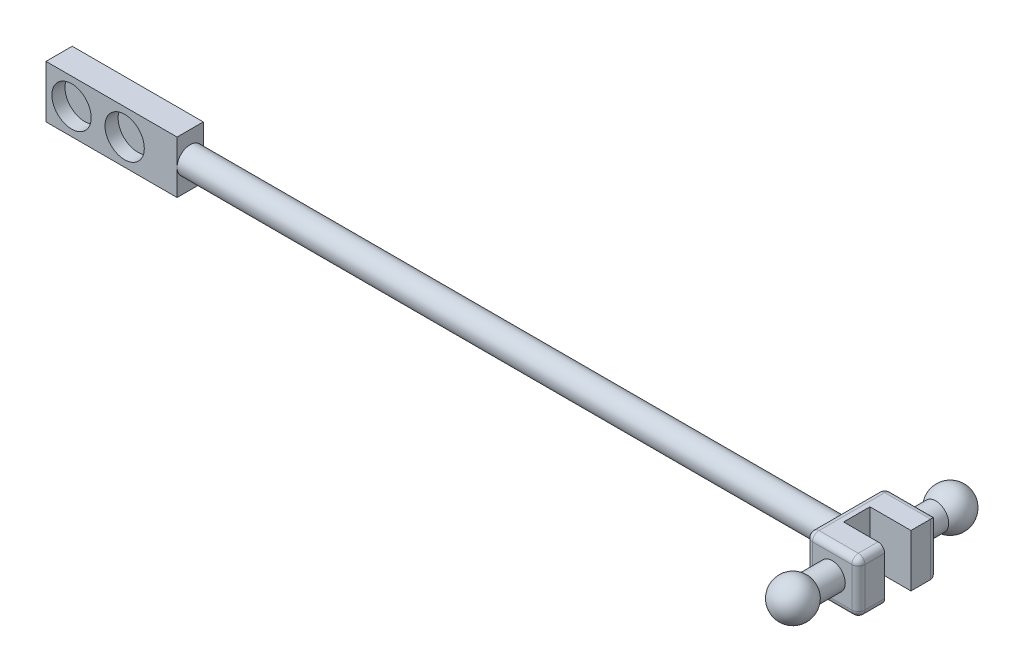
SolidWorks part; units mm, degrees
ref_plane "Front Plane" through (0, 0, 0) normal (0, 0, 1) x (1, 0, 0)
ref_plane "Top Plane" through (0, 0, 0) normal (0, 1, 0) x (1, 0, 0)
ref_plane "Right Plane" through (0, 0, 0) normal (1, 0, 0) x (0, 0, -1)
sketch "Sketch1" plane through (0, 0, 0) normal (0, 0, 1) x (1, 0, 0)
  line L0 (-95.2278, -7.0496) -> (-85.2278, -7.0496)
  line L1 (-85.2278, -7.0496) -> (-85.2278, -11.0496)
  line L2 (-95.2278, -7.0496) -> (-95.2278, -11.0496)
  line L3 (-1049.8238, -9.0496) -> (48950.1762, -9.0496) construction
  line L4 (-95.2278, -11.0496) -> (-85.2278, -11.0496)
  point P7 (-85.2278, -9.0496)
  point P8 (-95.2278, -9.0496)
  dimension "D1" = 10
  dimension "D2" = 4
extrude "Boss-Extrude1" add sketch "Sketch1" along normal blind 2
sketch "Sketch2" plane through (0, 0, 2) normal (0, 0, 1) x (1, 0, 0)
  line L0 (-1095.2278, -9.0496) -> (48904.7722, -9.0496) construction
  line L1 (-95.2278, -7.0496) -> (-95.2278, -11.0496) construction
  line L2 (-1093.104, -7.0496) -> (48906.896, -7.0496) construction
  line L4 (-1093.5994, -11.0496) -> (48906.4006, -11.0496) construction
  line L6 (-96.052, -1008.6262) -> (-96.052, 48991.3738) construction
  line L7 (-85.2278, -1008.4185) -> (-85.2278, 48991.5815) construction
  circle A0 centre (-93.2798, -9.0496) radius 1.5
  circle A1 centre (-89.2278, -9.0496) radius 1.5
  point P5 (-95.2278, -9.0496)
  dimension "D1" = 3
  dimension "D2" = 3
  dimension "D3" = 6
extrude "Cut-Extrude1" cut sketch "Sketch2" against normal blind 1
sketch "Sketch3" plane through (-85.2278, 0, 0) normal (1, 0, 0) x (0, 0, -1)
  line L0 (-1001.6849, -7.0496) -> (48998.3151, -7.0496) construction
  line L2 (-1001.6055, -11.0496) -> (48998.3945, -11.0496) construction
  line L4 (-2, -1007.9826) -> (-2, 48992.0174) construction
  line L6 (0, -1008.4988) -> (0, 48991.5012) construction
  line L8 (-1, -1007.7047) -> (-1, 48992.2953) construction
  line L9 (-1000.9404, -9.0496) -> (48999.0596, -9.0496) construction
  circle A0 centre (-1, -9.0546) radius 1
  dimension "D5" = 2
  dimension "D1" = 4
  dimension "D2" = 2
  dimension "D3" = 2
  dimension "D4" = 1
extrude "Boss-Extrude2" add sketch "Sketch3" along normal blind 50
sketch "Sketch4" plane through (0, -7.0496, 0) normal (0, 1, 0) x (1, 0, 0)
  line L0 (-1085.2278, -1) -> (48914.7722, -1) construction
  line L1 (-85.2278, -2) -> (-85.2278, 0) construction
  line L2 (-1044.3096, 0) -> (48955.6904, 0) construction
  line L4 (-1043.673, -2.0104) -> (48956.327, -2.0104) construction
  line L6 (-1049.1637, 2.6308) -> (48950.8363, 2.6308) construction
  line L7 (-1049.7207, -5.8041) -> (48950.2793, -5.8041) construction
  line L8 (-35.2381, -1001) -> (-35.2381, 48999) construction
  line L9 (-35.2278, -1000.9783) -> (-35.2278, 48999.0217) construction
  line L11 (-16.572, -998.6722) -> (-16.572, 49001.3278) construction
  line L12 (-19.917, -998.6722) -> (-19.917, 49001.3278) construction
  line L13 (-23.8815, -998.6722) -> (-23.8815, 49001.3278) construction
  line L14 (-35.2381, 0) -> (-35.2381, 2)
  line L15 (-35.2381, 2) -> (-31.2381, 2)
  line L16 (-31.2381, 2) -> (-31.2381, 0)
  line L17 (-31.2381, 0) -> (-34.3671, 0)
  line L18 (-34.3671, 0) -> (-34.3671, -2.0104)
  line L19 (-34.3671, -2.0104) -> (-31.2381, -2.0104)
  line L20 (-31.2381, -2.0104) -> (-31.2381, -4.0104)
  line L21 (-35.2381, -4.0104) -> (-31.2381, -4.0104)
  line L22 (-35.2381, -4.0104) -> (-35.2381, 0)
  point P5 (-85.2278, -1)
  dimension "D1" = 2
  dimension "D2" = 2
  dimension "D3" = 4
  dimension "D4" = 4
extrude "Boss-Extrude3" add sketch "Sketch4" against normal blind 4
fillet "Fillet1" radius 0.5 9 edges at (-35.2381, -9.0496, -2) (-33.2381, -11.0496, -2) (-31.2381, -9.0496, -2) (-33.2381, -7.0496, -2) (-33.2381, -11.0496, 4.0104) (-35.2381, -11.0496, 1.0052) (-33.2381, -7.0496, 4.0104) (-35.2381, -9.0496, 4.0104) (-35.2381, -7.0496, 1.0052)
sketch "Sketch6" plane through (0, 0, -2) normal (0, 0, -1) x (-1, 0, 0)
  line L0 (-967.5337, -7.5496) -> (49032.4663, -7.5496) construction
  line L2 (-967.2006, -10.5496) -> (49032.7994, -10.5496) construction
  line L4 (31.7381, -1008.6415) -> (31.7381, 48991.3585) construction
  line L6 (34.7381, -1009.0496) -> (34.7381, 48990.9504) construction
  line L7 (34.7381, -10.5496) -> (34.7381, -7.5496) construction
  line L8 (33.2381, -1008.7843) -> (33.2381, 48991.2157) construction
  line L9 (-967.4703, -9.0496) -> (49032.5297, -9.0496) construction
  circle A0 centre (33.2381, -9.0381) radius 1
  point P11 (34.7381, -9.0496)
  dimension "D5" = 2
  dimension "D1" = 3
  dimension "D2" = 1.5
  dimension "D3" = 3
  dimension "D4" = 1.5
sketch "Sketch7" plane through (0, -7.0496, 0) normal (0, 1, 0) x (1, 0, 0)
  line L0 (-1035.2381, -1.0052) -> (48964.7619, -1.0052) construction
  line L1 (-35.2381, -3.5104) -> (-35.2381, 1.5) construction
  point P5 (-35.2381, -1.0052)
sketch3d "3DSketch1" plane through (0, 0, 0) normal (0, 0, 1) x (1, 0, 0)
extrude "Boss-Extrude6" add sketch "Sketch6" along normal blind 3
sketch "Sketch16" plane through (0, 0, -5) normal (0, 0, -1) x (-1, 0, 0)
  line L0 (33.2381, -1009.0381) -> (33.2381, 48990.9619) construction
  line L1 (34.7381, -7.5496) -> (31.7381, -7.5496) construction
  line L2 (31.7381, -10.5496) -> (34.7381, -10.5496) construction
  line L3 (33.2381, -7.5496) -> (33.2381, -10.5496)
  arc A0 (33.2381, -7.5496) -> (33.2381, -10.5496) centre (33.2381, -9.0496) cw
  dimension "D1" = 1.5
revolve "Revolve10" add sketch "Sketch16" angle 360 about L0
fillet "Fillet2" radius 0.5 5 edges at (-31.2381, -11.0496, 2.7604) (-31.2381, -10.9032, 3.8639) (-31.2381, -7.0496, 2.7604) (-31.2381, -7.1961, 3.8639) (-31.2381, -9.0496, 4.0104)
sketch "Sketch18" plane through (0, 0, 4.0104) normal (0, 0, 1) x (1, 0, 0)
  circle A0 centre (-33.2343, -9.0307) radius 0.9965
extrude "Boss-Extrude7" add sketch "Sketch18" along normal blind 3
sketch "Sketch20" plane through (0, 0, 7.0104) normal (0, 0, 1) x (1, 0, 0)
  line L0 (-33.2343, -1009.0307) -> (-33.2343, 48990.9693) construction
  line L1 (-33.2343, -7.5507) -> (-33.2343, -10.5107)
  arc A0 (-33.2343, -10.5107) -> (-33.2343, -7.5507) centre (-33.2343, -9.0307) ccw
revolve "Revolve22" add sketch "Sketch20" angle 360 about L0
